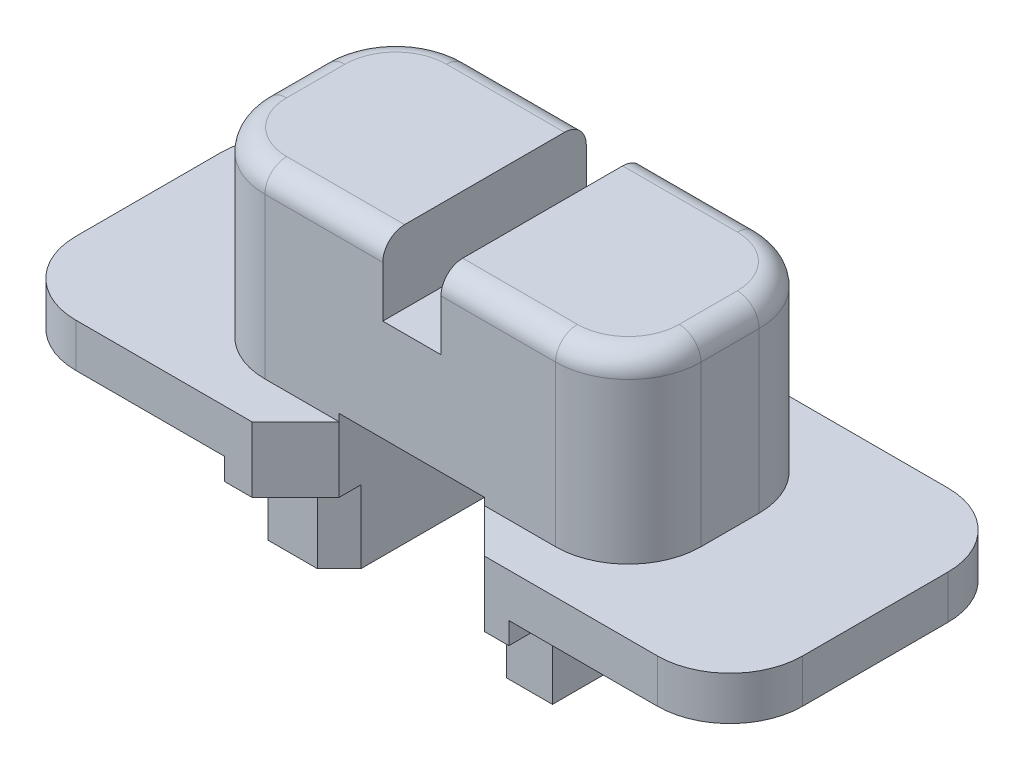
SolidWorks part; units mm, degrees
ref_plane "前视基准面" through (0, 0, 0) normal (0, 0, 1) x (1, 0, 0)
ref_plane "上视基准面" through (0, 0, 0) normal (0, 1, 0) x (1, 0, 0)
ref_plane "右视基准面" through (0, 0, 0) normal (1, 0, 0) x (0, 0, -1)
sketch "草图1" plane through (0, 0, 0) normal (0, 1, 0) x (1, 0, 0)
  line L1 (-4.5475, 2) -> (5.4525, 2)
  line L2 (-4.5475, 2) -> (-4.5475, -2)
  line L3 (-4.5475, -2) -> (5.4525, -2)
  line L4 (5.4525, 2) -> (5.4525, -2)
  line L5 (-4.5475, 2) -> (5.4525, -2) construction
  line L6 (-4.5475, -2) -> (5.4525, 2) construction
  point P0 (0.4525, 0)
  dimension "D1" = 10
  dimension "D2" = 4
extrude "凸台-拉伸1" add sketch "草图1" along normal blind 0.6
sketch "草图2" plane through (0, 0.6, 0) normal (0, 1, 0) x (1, 0, 0)
  line L1 (-2.5475, 1.4) -> (3.4525, 1.4)
  line L2 (-2.5475, 1.4) -> (-2.5475, -1.4)
  line L3 (-2.5475, -1.4) -> (3.4525, -1.4)
  line L4 (3.4525, 1.4) -> (3.4525, -1.4)
  line L5 (-2.5475, 1.4) -> (3.4525, -1.4) construction
  line L6 (-2.5475, -1.4) -> (3.4525, 1.4) construction
  line L7 (5.4525, -2) -> (5.4525, 2) construction
  point P0 (0.4525, 0)
  point P12 (5.4525, 0)
  dimension "D1" = 2.8
  dimension "D2" = 6
extrude "凸台-拉伸2" add sketch "草图2" along normal blind 2.5
fillet "圆角1" radius 1 8 edges at (-4.5475, 0.3, 2) (-2.5475, 1.85, 1.4) (5.4525, 0.3, 2) (3.4525, 1.85, 1.4) (-2.5475, 1.85, -1.4) (3.4525, 1.85, -1.4) (5.4525, 0.3, -2) (-4.5475, 0.3, -2)
sketch "草图7" plane through (0, 0, 1.4) normal (0, 0, 1) x (1, 0, 0)
  line L0 (-1.5475, 3.1) -> (2.4525, 3.1) construction
  line L1 (0.8748, 2.1) -> (0.0748, 2.1)
  line L2 (0.8748, 2.1) -> (0.8748, 3.1)
  line L3 (0.8748, 3.1) -> (0.0748, 3.1)
  line L4 (0.0748, 2.1) -> (0.0748, 3.1)
  line L5 (0.8748, 2.1) -> (0.0748, 3.1) construction
  line L6 (0.8748, 3.1) -> (0.0748, 2.1) construction
  point P0 (0.4748, 2.6)
  dimension "D1" = 0.8
extrude "切除-拉伸2" cut sketch "草图7" against normal up to next and the other way through all
sketch "草图8" plane through (0, 0, 0) normal (0, -1, 0) x (1, 0, 0)
  line L0 (-3.5475, 2) -> (4.4525, 2) construction
  line L1 (-1.5043, 2) -> (2.4092, 2)
  line L2 (-1.5043, 2) -> (-1.5043, -2)
  line L3 (-1.5043, -2) -> (2.4092, -2)
  line L4 (2.4092, 2) -> (2.4092, -2)
  line L5 (-1.5043, 2) -> (2.4092, -2) construction
  line L6 (-1.5043, -2) -> (2.4092, 2) construction
  line L7 (4.4525, -2) -> (-3.5475, -2) construction
  point P0 (0.4525, 0)
  point P7 (0.4525, 2)
extrude "凸台-拉伸3" add sketch "草图8" along normal blind 0.3
sketch "草图9" plane through (0, 0, -2) normal (0, 0, -1) x (-1, 0, 0)
  line L0 (1.5043, -0.3) -> (-2.4092, -0.3) construction
  line L1 (-1.4748, -0.3) -> (0.5252, -0.3)
  line L2 (-1.4748, -0.3) -> (-1.4748, 0.7)
  line L3 (-1.4748, 0.7) -> (0.5252, 0.7)
  line L4 (0.5252, -0.3) -> (0.5252, 0.7)
  line L5 (-0.0748, 2.1) -> (-0.8748, 2.1) construction
  point P6 (-0.4748, 0.7)
  point P9 (-0.4748, 2.1)
  dimension "D1" = 2
  dimension "D2" = 1
extrude "切除-拉伸3" cut sketch "草图9" against normal up to next
chamfer "倒角2" distance 0.6 angle 45 4 edges at (-0.5252, 0.15, 2) (-0.5252, 0.15, -2) (1.4748, 0.15, -2) (1.4748, 0.15, 2)
fillet "圆角2" radius 0.3 10 edges at (1.6636, 3.1, 1.4) (3.1596, 3.1, 1.1071) (3.4525, 3.1, 0) (1.6636, 3.1, -1.4) (-0.7364, 3.1, -1.4) (-0.7364, 3.1, 1.4) (-2.2546, 3.1, 1.1071) (-2.5475, 3.1, 0) (3.1596, 3.1, -1.1071) (-2.2546, 3.1, -1.1071)
sketch "草图10" plane through (0, -0.3, 0) normal (0, -1, 0) x (1, 0, 0)
  line L0 (-1.1252, -2) -> (-0.5252, -1.4) construction
  line L1 (-0.5252, -1.4) -> (-1.5043, -1.4)
  line L2 (-0.5252, -1.4) -> (-0.5252, 1.4)
  line L3 (-0.5252, 1.4) -> (-1.5043, 1.4)
  line L4 (-1.5043, -1.4) -> (-1.5043, 1.4)
  line L5 (-0.5252, 1.4) -> (-0.5252, -1.4) construction
  line L6 (-1.5043, 2) -> (-1.5043, -2) construction
  line L7 (1.4748, 1.4) -> (1.4748, -1.4) construction
  line L8 (1.4748, -1.4) -> (2.4092, -1.4)
  line L9 (1.4748, -1.4) -> (1.4748, 1.4)
  line L10 (1.4748, 1.4) -> (2.4092, 1.4)
  line L11 (2.4092, -1.4) -> (2.4092, 1.4)
  line L12 (2.4092, -2) -> (2.4092, 2) construction
  point P18 (0, 0)
  point P20 (0, 0)
extrude "凸台-拉伸4" add sketch "草图10" along normal blind 1
chamfer "倒角3" distance 0.3 angle 45 4 edges at (1.4748, -0.8, -1.4) (-0.5252, -0.8, -1.4) (1.4748, -0.8, 1.4) (-0.5252, -0.8, 1.4)
